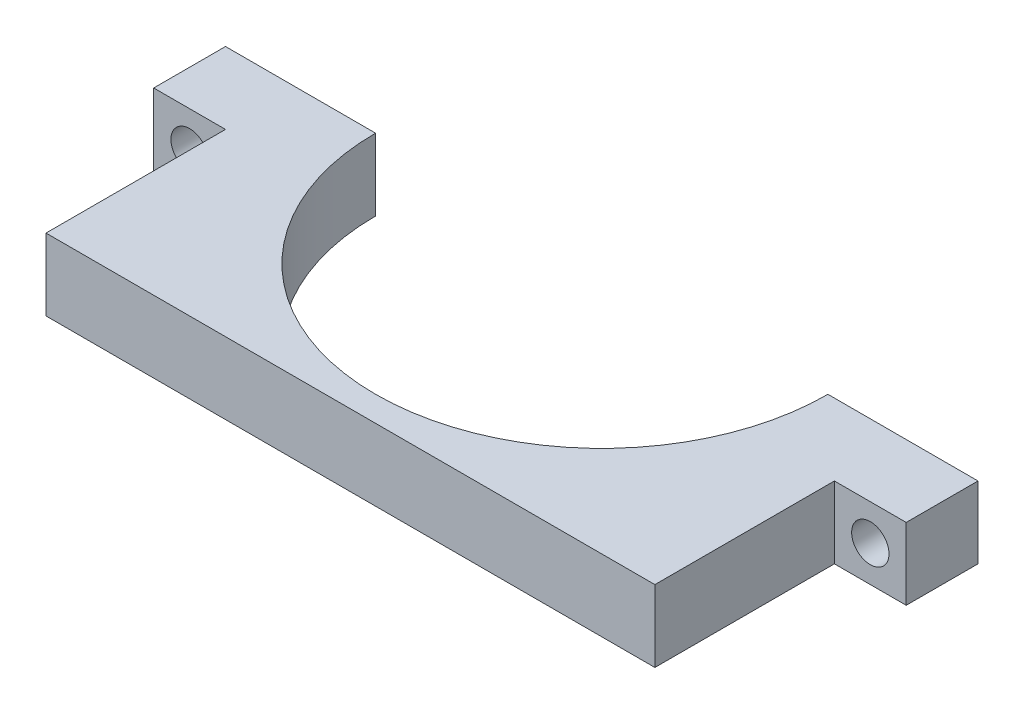
SolidWorks part; units mm, degrees
ref_plane "Front Plane" through (0, 0, 0) normal (0, 0, 1) x (1, 0, 0)
ref_plane "Top Plane" through (0, 0, 0) normal (0, 1, 0) x (1, 0, 0)
ref_plane "Right Plane" through (0, 0, 0) normal (1, 0, 0) x (0, 0, -1)
sketch "Sketch1" plane through (0, 0, 0) normal (0, 1, 0) x (1, 0, 0)
  line L0 (0, 0) -> (-19.4034, 0) construction
  line L1 (-34.9248, 0) -> (-61.4678, 0)
  line L2 (-61.4678, 0) -> (-61.4678, -12.7)
  line L3 (-61.4678, -12.7) -> (-48.7678, -12.7)
  line L4 (-48.7678, -12.7) -> (-48.7678, -44.45)
  line L5 (-48.7678, -44.45) -> (58.9282, -44.45)
  line L6 (58.9282, -44.45) -> (58.9282, -12.7)
  line L7 (58.9282, -12.7) -> (71.6282, -12.7)
  line L8 (71.6282, -12.7) -> (71.6282, 0)
  line L9 (71.6282, 0) -> (45.0852, 0)
  arc A0 (-34.9248, 0) -> (45.0852, 0) centre (5.0802, 0) ccw
  dimension "D1" = 26.543
  dimension "D2" = 26.543
  dimension "D3" = 12.7
  dimension "D4" = 12.7
  dimension "D5" = 12.7
  dimension "D6" = 12.7
  dimension "D7" = 31.75
  dimension "D8" = 107.696
  dimension "D9" = 80.01
extrude "Boss-Extrude1" add sketch "Sketch1" along normal blind 12.7
sketch "Sketch2" plane through (0, 0, 12.7) normal (0, 0, 1) x (1, 0, 0)
  line L0 (71.6282, 12.7) -> (71.6282, 0) construction
  line L1 (58.9282, 0) -> (71.6282, 0) construction
  line L2 (-61.4678, 0) -> (-48.7678, 0) construction
  line L3 (-61.4678, 12.7) -> (-61.4678, 0) construction
  circle A0 centre (65.2782, 6.35) radius 3.302
  circle A1 centre (-55.1178, 6.35) radius 3.302
  dimension "D1" = 6.35
  dimension "D2" = 6.35
  dimension "D3" = 6.35
  dimension "D4" = 6.35
extrude "Cut-Extrude1" cut sketch "Sketch2" against normal up to next
